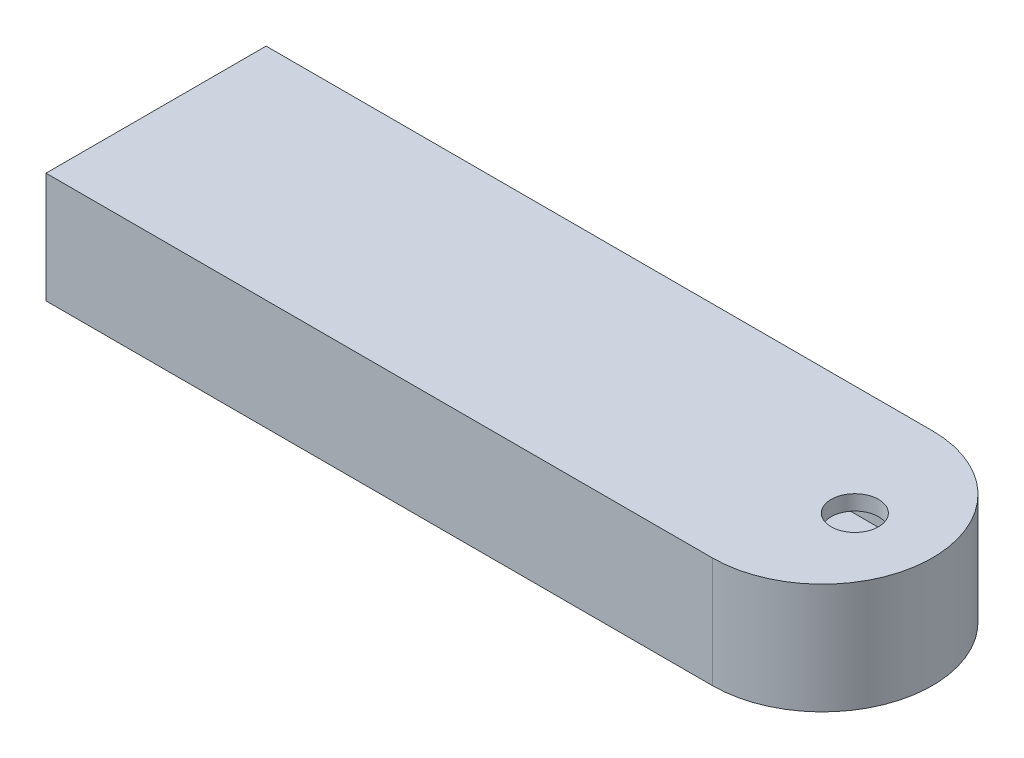
SolidWorks part; units mm, degrees
ref_plane "Front Plane" through (0, 0, 0) normal (0, 0, 1) x (1, 0, 0)
ref_plane "Top Plane" through (0, 0, 0) normal (0, 1, 0) x (1, 0, 0)
ref_plane "Right Plane" through (0, 0, 0) normal (1, 0, 0) x (0, 0, -1)
sketch "Sketch1" plane through (0, 0, 0) normal (0, 1, 0) x (1, 0, 0)
  line L1 (-57.3617, 14.139) -> (27.1883, 14.139)
  line L2 (-57.3617, 14.139) -> (-57.3617, -11.111)
  line L3 (-57.3617, -11.111) -> (27.1883, -11.111)
  line L4 (27.1883, 14.139) -> (27.1883, -11.111)
  line L5 (-57.3617, 14.139) -> (27.1883, -11.111) construction
  line L6 (-57.3617, -11.111) -> (27.1883, 14.139) construction
  line L11 (-59.3617, 16.139) -> (29.1883, 16.139)
  line L12 (-59.3617, 16.139) -> (-59.3617, -13.111)
  line L17 (-59.3617, -13.111) -> (29.1883, -13.111)
  line L18 (29.1883, 16.139) -> (29.1883, -13.111)
  line L19 (-59.3617, 16.139) -> (29.1883, -13.111) construction
  line L20 (-59.3617, -13.111) -> (29.1883, 16.139) construction
  circle A1 centre (27.1883, 1.514) radius 12.625
  circle A2 centre (33.4983, 1.514) radius 3.155
  circle A3 centre (29.1883, 1.514) radius 14.625
  point P0 (-15.0867, 1.514)
  point P5 (-15.0867, 1.514)
  point P8 (-15.0867, 1.514)
  dimension "D5" = 6.31
  dimension "D1" = 25.25
  dimension "D2" = 84.55
  dimension "D3" = 29.25
  dimension "D4" = 88.55
  dimension "D6" = 6.31
extrude "Boss-Extrude7" add sketch "Sketch1" along normal blind 14.7 contours A2 | L12 L17 L18 L11 | A3
shell "Shell1" thickness 2
sketch "Sketch4" plane through (-59.3617, 0, 0) normal (-1, 0, 0) x (0, 0, 1)
  line L0 (11.111, 12.7) -> (11.111, 2) construction
  line L1 (-14.139, 2) -> (11.111, 2) construction
  line L2 (-14.139, 12.7) -> (-14.139, 2) construction
  line L3 (-14.139, 12.7) -> (11.111, 12.7) construction
  line L4 (11.111, 12.7) -> (11.111, 2)
  line L5 (-14.139, 2) -> (11.111, 2)
  line L6 (-14.139, 12.7) -> (-14.139, 2)
  line L7 (-14.139, 12.7) -> (11.111, 12.7)
extrude "Cut-Extrude5" cut sketch "Sketch4" against normal up to body
